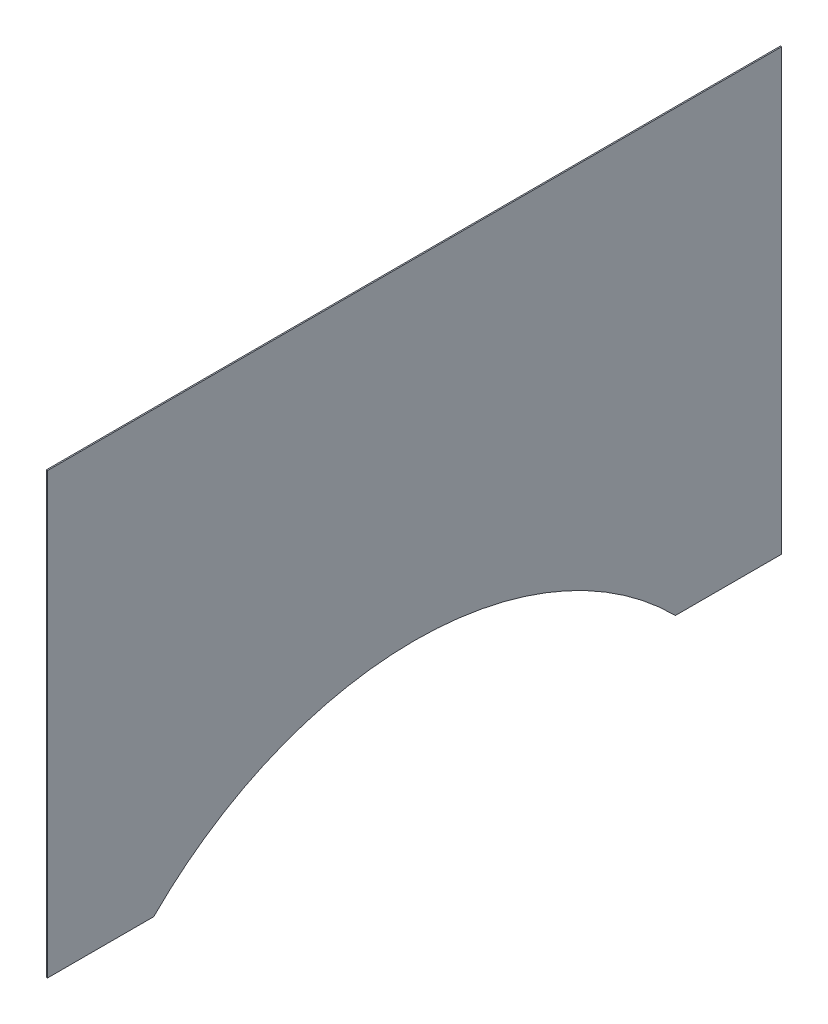
SolidWorks part; units mm, degrees
ref_plane "Front Plane" through (0, 0, 0) normal (0, 0, 1) x (1, 0, 0)
ref_plane "Top Plane" through (0, 0, 0) normal (0, 1, 0) x (1, 0, 0)
ref_plane "Right Plane" through (0, 0, 0) normal (1, 0, 0) x (0, 0, -1)
sketch "Sketch1" plane through (0, 0, 0) normal (1, 0, 0) x (0, 0, -1)
  line L0 (-241.3, 217.4207) -> (241.3, 217.4207)
  line L1 (241.3, 217.4207) -> (241.3, -71.5043)
  line L2 (241.3, -71.5043) -> (171.45, -71.5043)
  line L3 (-171.45, -71.5043) -> (-241.3, -71.5043)
  line L4 (-241.3, -71.5043) -> (-241.3, 217.4207)
  arc A0 (171.45, -71.5043) -> (-171.45, -71.5043) centre (0, -241.3) ccw
  dimension "D3" = 241.3
  dimension "D1" = 482.6
  dimension "D2" = 288.925
  dimension "D4" = 69.85
extrude "Boss-Extrude1" add sketch "Sketch1" along normal blind 0.7937
